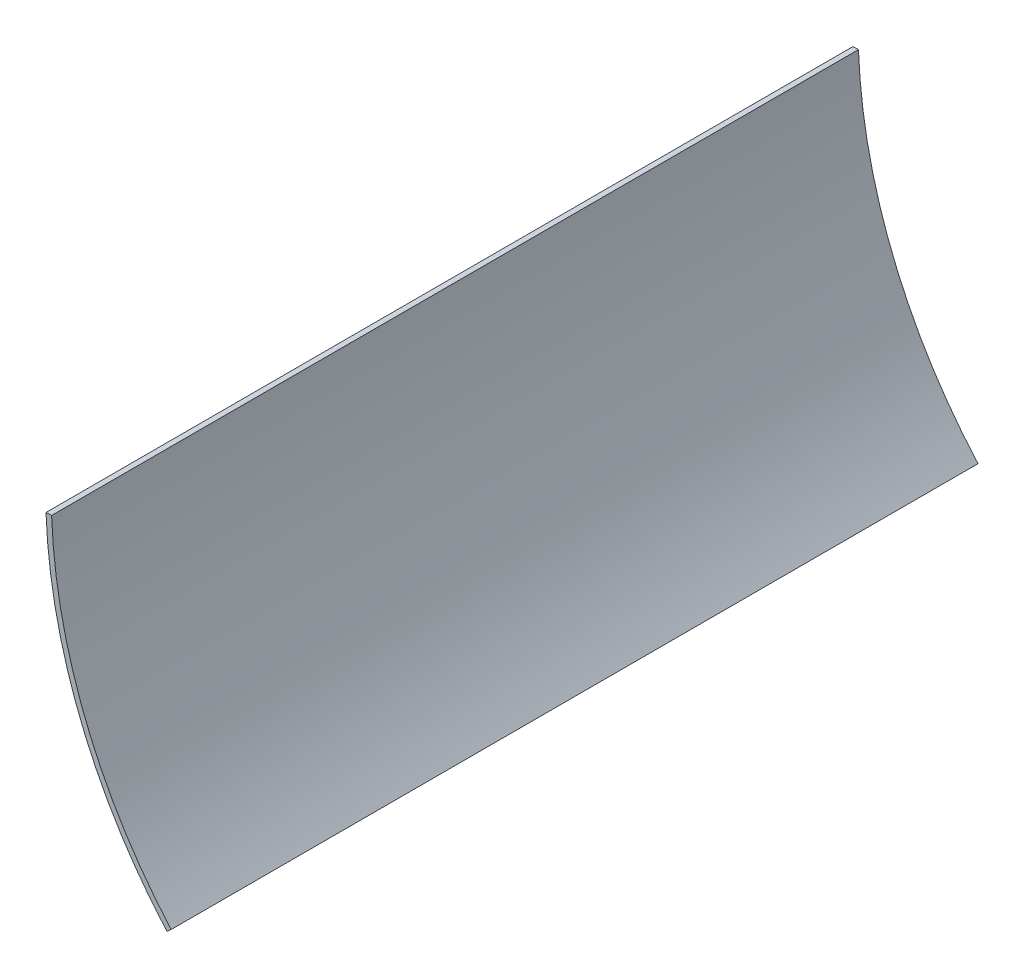
SolidWorks part; units mm, degrees
ref_plane "Front Plane" through (0, 0, 0) normal (0, 0, 1) x (1, 0, 0)
ref_plane "Top Plane" through (0, 0, 0) normal (0, 1, 0) x (1, 0, 0)
ref_plane "Right Plane" through (0, 0, 0) normal (1, 0, 0) x (0, 0, -1)
sketch "Sketch1" plane through (0, 0, 0) normal (0, 0, 1) x (1, 0, 0)
  arc A0 (0, 0) -> (101.6, -254) centre (406.1184, 15.1273) ccw
  dimension "D1" = 406.4
  dimension "D2" = 101.6
  dimension "D3" = 254
extrude "Extrude-Thin1" add sketch "Sketch1" along normal mid plane 685.8 thin
sketch "Sketch2" plane through (0, 0, 342.9) normal (0, 0, 1) x (1, 0, 0)
  line L0 (-9.289, -72.4697) -> (4.3954, -72.4697)
  line L1 (-9.289, -97.8697) -> (10.7878, -97.8697)
  arc A1 (-9.289, -72.4697) -> (-9.289, -97.8697) centre (-9.289, -85.1697) ccw
  arc A2 (-4.7592, -0.1773) -> (98.0314, -257.1538) centre (406.1184, 15.1273) ccw construction
  circle A4 centre (-9.289, -85.1697) radius 3.175 construction
  arc A5 (4.3954, -72.4697) -> (10.7878, -97.8697) centre (406.1184, 15.1273) ccw
  point P9 (0, 0)
  point P11 (0, 0)
  dimension "D1" = 25.4
extrude "Boss-Extrude1" add sketch "Sketch2" against normal offset from surface (279.4 mm away) 203.2 from offset 203.2 up to face at (37.6463, -132.2615, -342.9) offset against normal yes
sketch "Sketch3" plane through (0, 0, 139.7) normal (0, 0, 1) x (1, 0, 0)
  line L2 (-9.289, -97.8697) -> (10.7878, -97.8697)
  line L3 (4.3954, -72.4697) -> (-9.289, -72.4697)
  line L4 (-9.289, -97.8697) -> (10.7878, -97.8697)
  line L5 (4.3954, -72.4697) -> (-9.289, -72.4697)
  arc A2 (-9.289, -72.4697) -> (-9.289, -97.8697) centre (-9.289, -85.1697) ccw
  arc A3 (4.3954, -72.4697) -> (10.7878, -97.8697) centre (406.1184, 15.1273) ccw
  arc A4 (-9.289, -72.4697) -> (-9.289, -97.8697) centre (-9.289, -85.1697) ccw
  arc A5 (4.3954, -72.4697) -> (10.7878, -97.8697) centre (406.1184, 15.1273) ccw
  dimension "D1" = 0
extrude "Cut-Extrude1" cut sketch "Sketch3" against normal offset from surface (203.2 mm away) 38.1 from offset 38.1 up to face at (-4.0743, -85.1824, -139.7) offset against normal yes
sketch "Sketch4" plane through (0, 0, -101.6) normal (0, 0, 1) x (1, 0, 0)
  circle A0 centre (-9.289, -85.1697) radius 3.048
  arc A1 (-9.289, -72.4697) -> (-9.289, -97.8697) centre (-9.289, -85.1697) ccw construction
  circle A2 centre (-9.289, -85.1697) radius 12.7
  arc A3 (-9.289, -72.4697) -> (-9.289, -97.8697) centre (-9.289, -85.1697) ccw construction
  arc M2 (-9.289, -72.4697) -> (-9.289, -97.8697) centre (-9.289, -85.1697) ccw
  dimension "D1" = 6.096
extrude "Cut-Extrude2" cut sketch "Sketch4" against normal offset from surface (19.05 mm away) 9.525 from offset 9.525 contours A2 A0 M2 up to face at (-4.0743, -85.1824, -139.7) offset against normal yes
sketch "Sketch5" plane through (0, 0, 101.6) normal (0, 0, -1) x (-1, 0, 0)
  circle A0 centre (9.289, -85.1697) radius 3.048
  arc A1 (9.289, -97.8697) -> (9.289, -72.4697) centre (9.289, -85.1697) ccw construction
  circle A2 centre (9.289, -85.1697) radius 12.7
  arc M3 (9.289, -97.8697) -> (9.289, -72.4697) centre (9.289, -85.1697) ccw
  dimension "D1" = 6.096
extrude "Cut-Extrude3" cut sketch "Sketch5" against normal offset from surface (19.05 mm away) 9.525 from offset 9.525 contours A2 A0 M3 up to face at (-4.0743, -85.1824, 139.7)
